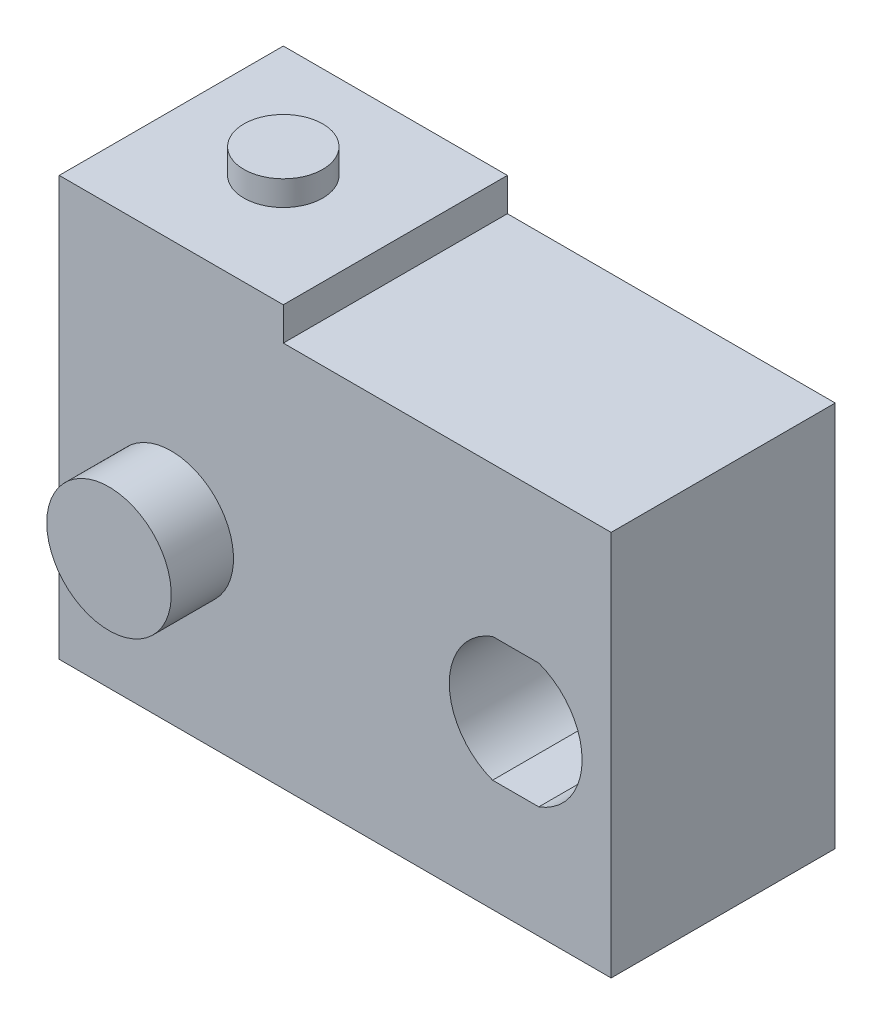
SolidWorks part; units mm, degrees
ref_plane "Front Plane" through (0, 0, 0) normal (0, 0, 1) x (1, 0, 0)
ref_plane "Top Plane" through (0, 0, 0) normal (0, 1, 0) x (1, 0, 0)
ref_plane "Right Plane" through (0, 0, 0) normal (1, 0, 0) x (0, 0, -1)
sketch "Sketch1" plane through (0, 0, 0) normal (0, 0, 1) x (1, 0, 0)
  line L0 (3.7932, 1.05) -> (4.9068, 1.05)
  line L1 (6.65, -4.65) -> (-6.65, -4.65)
  line L2 (6.65, -4.65) -> (6.65, 4.65)
  line L3 (6.65, 4.65) -> (-1.25, 4.65)
  line L4 (-6.65, -4.65) -> (-6.65, 4.65)
  line L5 (6.65, -4.65) -> (-6.65, 4.65) construction
  line L6 (6.65, 4.65) -> (-6.65, -4.65) construction
  line L7 (4.9068, -1.95) -> (3.7932, -1.95)
  line L8 (4.35, 1.05) -> (4.35, -0.45) construction
  line L9 (4.35, -0.45) -> (4.35, -1.95) construction
  line L10 (-6.65, 4.65) -> (-6.65, 5.45)
  line L11 (-6.65, 5.45) -> (-1.25, 5.45)
  line L12 (-1.25, 5.45) -> (-1.25, 4.65)
  arc A0 (3.7932, 1.05) -> (3.7932, -1.95) centre (4.35, -0.45) ccw
  arc A1 (4.9068, -1.95) -> (4.9068, 1.05) centre (4.35, -0.45) ccw
  point P0 (0, 0)
  dimension "D6" = 3.2
  dimension "D1" = 13.3
  dimension "D2" = 9.3
  dimension "D3" = 4.2
  dimension "D4" = 11
  dimension "D5" = 3
  dimension "D7" = 5.4
  dimension "D8" = 5.9
extrude "Boss-Extrude1" add sketch "Sketch1" along normal mid plane 5.4
sketch "Sketch3" plane through (0, 0, 0) normal (0, 0, 1) x (1, 0, 0)
  line L0 (-3.95, -0.45) -> (4.35, -0.45) construction
  circle A0 centre (-3.95, -0.45) radius 1.5
  dimension "D2" = 3
  dimension "D1" = 8.3
extrude "Boss-Extrude2" add sketch "Sketch3" along normal offset from surface 1.5 and the other way offset from surface (4.2 mm away) 1.5 up to face at (-0.4167, 1.8167, 2.7) offset beyond the face yes other way up to face at (-0.4167, 1.8167, -2.7)
sketch "Sketch4" plane through (0, 5.45, 0) normal (0, 1, 0) x (1, 0, 0)
  line L0 (-3.95, 0) -> (0, 0) construction
  line L5 (-5.45, -4.2) -> (-2.45, -4.2) construction
  line L6 (-5.45, -4.2) -> (-2.45, -4.2) construction
  line L7 (-3.95, -4.2) -> (-3.95, 0) construction
  circle A0 centre (-3.95, 0) radius 0.95
  dimension "D1" = 1.9
extrude "Boss-Extrude3" add sketch "Sketch4" along normal offset from surface (0.6 mm away) 10.7 contours A0 up to face at (0, -4.65, 0)
